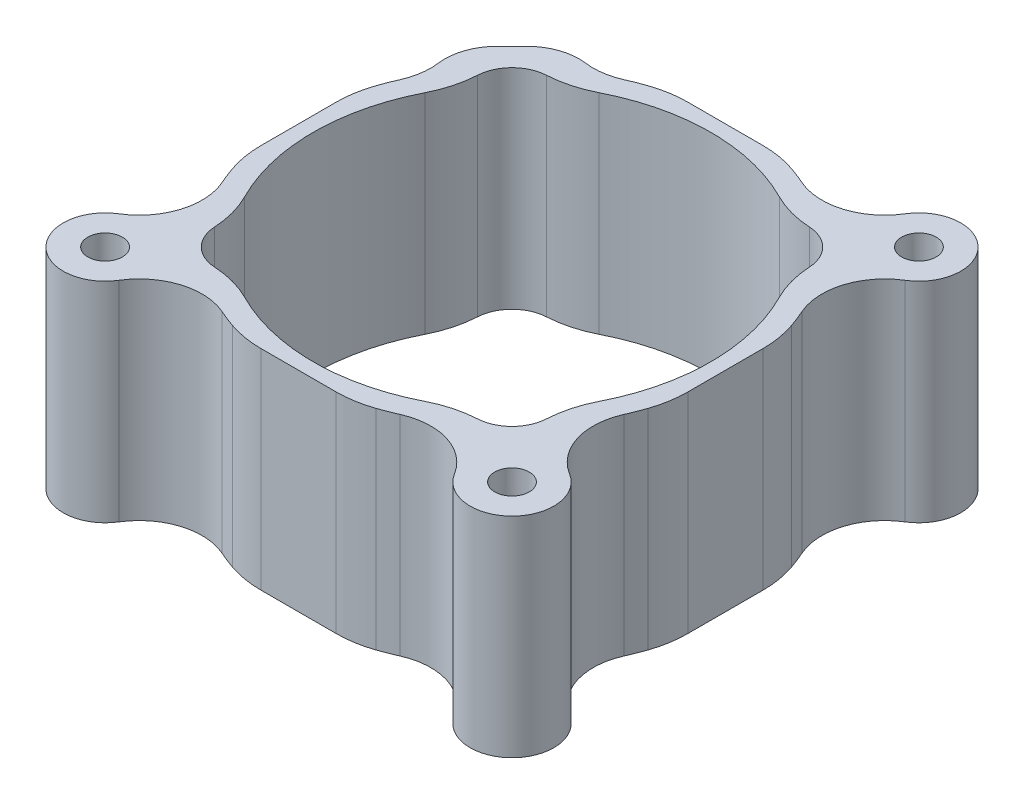
SolidWorks part; units mm, degrees
material "5052-H34"
ref_plane "正面" through (0, 0, 0) normal (0, 0, 1) x (1, 0, 0)
ref_plane "平面" through (0, 0, 0) normal (0, 1, 0) x (1, 0, 0)
ref_plane "右側面" through (0, 0, 0) normal (1, 0, 0) x (0, 0, -1)
sketch "ｽｹｯﾁ1" plane through (0, 0, 0) normal (0, 1, 0) x (1, 0, 0)
  line L0 (19.4454, 19.4454) -> (0, 0) construction
  line L3 (20.3961, 5) -> (20.3961, -5)
  line L4 (0, 0) -> (19, 0) construction
  line L5 (0, 0) -> (12.3744, 12.3744) construction
  line L6 (5, -20.3961) -> (-5, -20.3961)
  line L7 (-20.3961, -5) -> (-20.3961, 5)
  line L8 (-5, 20.3961) -> (5, 20.3961)
  arc A4 (10.9118, 15.5542) -> (-10.9118, 15.5542) centre (0, 0) ccw
  circle A9 centre (19.4454, 19.4454) radius 1.65
  arc A13 (19.2023, -8.5013) -> (20.3961, -5) centre (0, 0) ccw
  arc A14 (21.5427, 16.0394) -> (16.0394, 21.5427) centre (19.4454, 19.4454) ccw
  arc A18 (16.0394, 21.5427) -> (8.5013, 19.2023) centre (10.9302, 24.6887) cw
  arc A19 (21.5427, 16.0394) -> (19.2023, 8.5013) centre (24.6887, 10.9302) ccw
  arc A20 (16.0394, -21.5427) -> (21.5427, -16.0394) centre (19.4454, -19.4454) ccw
  arc A21 (16.0394, -21.5427) -> (8.5013, -19.2023) centre (10.9302, -24.6887) ccw
  circle A22 centre (19.4454, -19.4454) radius 1.65
  arc A23 (21.5427, -16.0394) -> (19.2023, -8.5013) centre (24.6887, -10.9302) cw
  arc A24 (-21.5427, -16.0394) -> (-16.0394, -21.5427) centre (-19.4454, -19.4454) ccw
  arc A25 (-21.5427, -16.0394) -> (-19.2023, -8.5013) centre (-24.6887, -10.9302) ccw
  circle A26 centre (-19.4454, -19.4454) radius 1.65
  arc A27 (-16.0394, -21.5427) -> (-8.5013, -19.2023) centre (-10.9302, -24.6887) cw
  arc A28 (-16.0394, 21.5427) -> (-21.5427, 16.0394) centre (-19.4454, 19.4454) ccw
  arc A29 (-16.0394, 21.5427) -> (-8.5013, 19.2023) centre (-10.9302, 24.6887) ccw
  circle A30 centre (-19.4454, 19.4454) radius 1.65
  arc A31 (-21.5427, 16.0394) -> (-19.2023, 8.5013) centre (-24.6887, 10.9302) cw
  arc A32 (-8.5013, -19.2023) -> (-5, -20.3961) centre (0, 0) ccw
  arc A33 (8.5013, 19.2023) -> (5, 20.3961) centre (0, 0) ccw
  arc A34 (-19.2023, 8.5013) -> (-20.3961, 5) centre (0, 0) ccw
  arc A35 (15.5542, 10.9118) -> (10.9118, 15.5542) centre (12.3744, 12.3744) ccw
  arc A36 (10.9118, -15.5542) -> (15.5542, -10.9118) centre (12.3744, -12.3744) ccw
  arc A37 (-15.5542, -10.9118) -> (-10.9118, -15.5542) centre (-12.3744, -12.3744) ccw
  arc A38 (-10.9118, 15.5542) -> (-15.5542, 10.9118) centre (-12.3744, 12.3744) ccw
  arc A39 (-15.5542, 10.9118) -> (-15.5542, -10.9118) centre (0, 0) ccw
  arc A40 (-10.9118, -15.5542) -> (10.9118, -15.5542) centre (0, 0) ccw
  arc A41 (15.5542, -10.9118) -> (15.5542, 10.9118) centre (0, 0) ccw
  arc A42 (20.3961, -5) -> (20.3961, 5) centre (0, 0) ccw construction
  arc A43 (20.3961, 5) -> (19.2023, 8.5013) centre (0, 0) ccw
  arc A44 (5, 20.3961) -> (-5, 20.3961) centre (0, 0) ccw construction
  arc A45 (-5, 20.3961) -> (-8.5013, 19.2023) centre (0, 0) ccw
  arc A46 (-20.3961, 5) -> (-20.3961, -5) centre (0, 0) ccw construction
  arc A47 (-20.3961, -5) -> (-19.2023, -8.5013) centre (0, 0) ccw
  arc A48 (-5, -20.3961) -> (5, -20.3961) centre (0, 0) ccw construction
  arc A49 (5, -20.3961) -> (8.5013, -19.2023) centre (0, 0) ccw
  point P17 (0, 0)
  point P22 (0, 0)
  point P24 (0, 0)
  point P33 (0, 0)
  point P62 (0, 0)
  dimension "D2" = 8
  dimension "D4" = 27.5
  dimension "D5" = 7
  dimension "D6" = 38
  dimension "D8" = 4
  dimension "D3" = 3.3
  dimension "D12" = 42
  dimension "D14" = 6
  dimension "D7" = 45
  dimension "D9" = 17.5
  dimension "D11" = 45
  dimension "D13" = 10
  dimension "D10" = 4
  dimension "D15" = 4
extrude "ﾎﾞｽ - 押し出し1" add sketch "ｽｹｯﾁ1" along normal blind 20
sketch "ｽｹｯﾁ4" plane through (0, 20, 0) normal (0, 1, 0) x (1, 0, 0)
  line L0 (-19.4246, 13.8094) -> (-13.8094, 19.4246)
  line L1 (-19.4454, 19.4454) -> (-16.617, 16.617) construction
  line L6 (5, 20.3961) -> (-5, 20.3961)
  line L7 (5, 20.3961) -> (-5, 20.3961)
  line L8 (-20.3961, 5) -> (-20.3961, -5)
  line L9 (-20.3961, 5) -> (-20.3961, -5)
  line L10 (-5, -20.3961) -> (5, -20.3961)
  line L11 (-5, -20.3961) -> (5, -20.3961)
  line L12 (20.3961, -5) -> (20.3961, 5)
  line L13 (20.3961, -5) -> (20.3961, 5)
  circle A0 centre (-19.4454, 19.4454) radius 4
  arc A1 (-19.2023, 8.5013) -> (-21.5427, 16.0394) centre (-24.6887, 10.9302) ccw construction
  arc A2 (-16.0394, 21.5427) -> (-8.5013, 19.2023) centre (-10.9302, 24.6887) ccw construction
  arc A19 (8.5013, 19.2023) -> (5, 20.3961) centre (0, 0) ccw
  arc A20 (8.5013, 19.2023) -> (5, 20.3961) centre (0, 0) ccw
  arc A21 (-19.2023, 8.5013) -> (-20.3961, 5) centre (0, 0) ccw
  arc A22 (-19.2023, 8.5013) -> (-20.3961, 5) centre (0, 0) ccw
  arc A23 (-8.5013, -19.2023) -> (-5, -20.3961) centre (0, 0) ccw
  arc A24 (-8.5013, -19.2023) -> (-5, -20.3961) centre (0, 0) ccw
  arc A25 (19.2023, -8.5013) -> (20.3961, -5) centre (0, 0) ccw
  arc A26 (19.2023, -8.5013) -> (20.3961, -5) centre (0, 0) ccw
  arc A31 (20.3961, 5) -> (19.2023, 8.5013) centre (0, 0) ccw
  arc A32 (20.3961, 5) -> (19.2023, 8.5013) centre (0, 0) ccw
  arc A33 (-5, 20.3961) -> (-8.5013, 19.2023) centre (0, 0) ccw
  arc A34 (-5, 20.3961) -> (-8.5013, 19.2023) centre (0, 0) ccw
  arc A35 (-20.3961, -5) -> (-19.2023, -8.5013) centre (0, 0) ccw
  arc A36 (-20.3961, -5) -> (-19.2023, -8.5013) centre (0, 0) ccw
  arc A37 (5, -20.3961) -> (8.5013, -19.2023) centre (0, 0) ccw
  arc A38 (5, -20.3961) -> (8.5013, -19.2023) centre (0, 0) ccw
  arc A55 (8.5013, 19.2023) -> (16.0394, 21.5427) centre (10.9302, 24.6887) ccw
  arc A66 (-16.0394, 21.5427) -> (-8.5013, 19.2023) centre (-10.9302, 24.6887) ccw
  arc A67 (-16.0394, 21.5427) -> (-21.5427, 16.0394) centre (-19.4454, 19.4454) ccw
  arc A68 (-19.2023, 8.5013) -> (-21.5427, 16.0394) centre (-24.6887, 10.9302) ccw
  arc A79 (-21.5427, -16.0394) -> (-19.2023, -8.5013) centre (-24.6887, -10.9302) ccw
  arc A80 (-21.5427, -16.0394) -> (-16.0394, -21.5427) centre (-19.4454, -19.4454) ccw
  arc A81 (-8.5013, -19.2023) -> (-16.0394, -21.5427) centre (-10.9302, -24.6887) ccw
  arc A92 (16.0394, -21.5427) -> (8.5013, -19.2023) centre (10.9302, -24.6887) ccw
  arc A93 (16.0394, -21.5427) -> (21.5427, -16.0394) centre (19.4454, -19.4454) ccw
  arc A94 (19.2023, -8.5013) -> (21.5427, -16.0394) centre (24.6887, -10.9302) ccw
  arc A105 (21.5427, 16.0394) -> (19.2023, 8.5013) centre (24.6887, 10.9302) ccw
  arc A106 (21.5427, 16.0394) -> (16.0394, 21.5427) centre (19.4454, 19.4454) ccw
  arc A107 (8.5013, 19.2023) -> (16.0394, 21.5427) centre (10.9302, 24.6887) ccw
  arc A118 (-16.0394, 21.5427) -> (-8.5013, 19.2023) centre (-10.9302, 24.6887) ccw
  arc A119 (-16.0394, 21.5427) -> (-21.5427, 16.0394) centre (-19.4454, 19.4454) ccw
  arc A120 (-19.2023, 8.5013) -> (-21.5427, 16.0394) centre (-24.6887, 10.9302) ccw
  arc A131 (-21.5427, -16.0394) -> (-19.2023, -8.5013) centre (-24.6887, -10.9302) ccw
  arc A132 (-21.5427, -16.0394) -> (-16.0394, -21.5427) centre (-19.4454, -19.4454) ccw
  arc A133 (-8.5013, -19.2023) -> (-16.0394, -21.5427) centre (-10.9302, -24.6887) ccw
  arc A144 (16.0394, -21.5427) -> (8.5013, -19.2023) centre (10.9302, -24.6887) ccw
  arc A145 (16.0394, -21.5427) -> (21.5427, -16.0394) centre (19.4454, -19.4454) ccw
  arc A146 (19.2023, -8.5013) -> (21.5427, -16.0394) centre (24.6887, -10.9302) ccw
  arc A157 (21.5427, 16.0394) -> (19.2023, 8.5013) centre (24.6887, 10.9302) ccw
  arc A158 (21.5427, 16.0394) -> (16.0394, 21.5427) centre (19.4454, 19.4454) ccw
  dimension "D1" = 0
extrude "ｶｯﾄ - 押し出し1" cut sketch "ｽｹｯﾁ4" against normal blind 15
fillet "ﾌｨﾚｯﾄ1" radius 10 16 edges at (10.9118, 10, -15.5542) (15.5542, 10, -10.9118) (15.5542, 10, 10.9118) (10.9118, 10, 15.5542) (-15.5542, 10, 10.9118) (-10.9118, 10, 15.5542) (-10.9118, 10, -15.5542) (-15.5542, 10, -10.9118) (-20.3961, 10, -5) (-20.3961, 10, 5) (-5, 10, -20.3961) (5, 10, -20.3961) (20.3961, 10, -5) (20.3961, 10, 5) (-5, 10, 20.3961) (5, 10, 20.3961)
fillet "ﾌｨﾚｯﾄ2" radius 5 2 edges at (-13.8094, 12.5, -19.4246) (-19.4246, 12.5, -13.8094)
